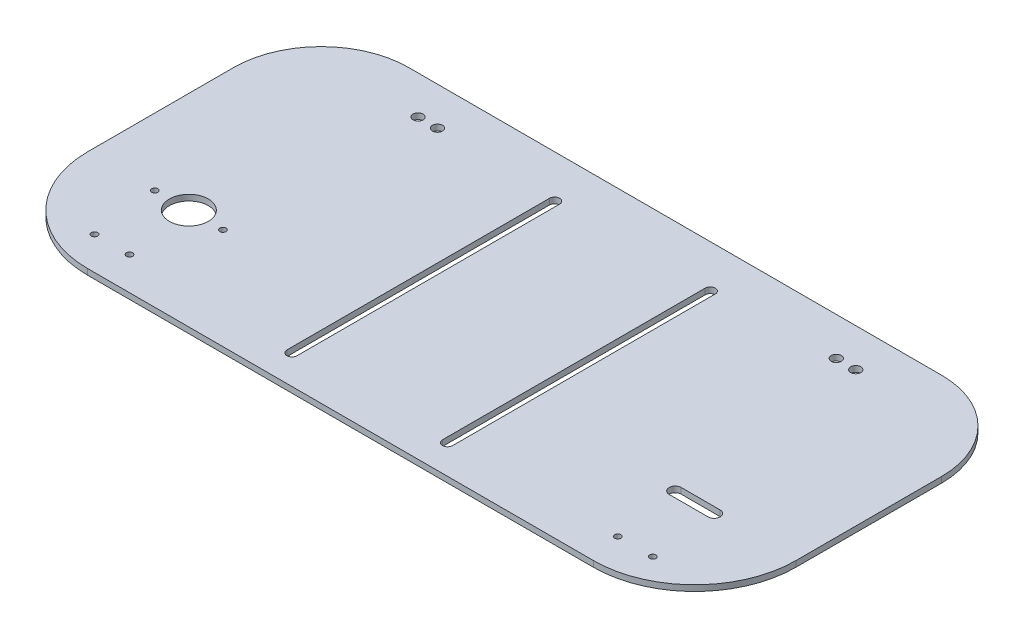
SolidWorks part; units mm, degrees
ref_plane "Front Plane" through (0, 0, 0) normal (0, 0, 1) x (1, 0, 0)
ref_plane "Top Plane" through (0, 0, 0) normal (0, 1, 0) x (1, 0, 0)
ref_plane "Right Plane" through (0, 0, 0) normal (1, 0, 0) x (0, 0, -1)
sketch "Sketch1" plane through (0, 0, 0) normal (0, 1, 0) x (1, 0, 0)
  line L0 (0, 0) -> (260, 0) construction
  line L5 (0, 52) -> (260, 52)
  line L6 (0, -52) -> (260, -52)
  line L7 (270, 0) -> (250, 0) construction
  line L8 (270, -3.1) -> (250, -3.1)
  line L9 (270, 3.1) -> (250, 3.1)
  line L11 (-52, 0) -> (312, 0) construction
  line L12 (-52, 0) -> (-52, 120)
  line L13 (-52, 120) -> (312, 120)
  line L14 (312, 0) -> (312, 120)
  arc A0 (0, 52) -> (0, -52) centre (0, 0) ccw
  arc A1 (260, -52) -> (260, 52) centre (260, 0) ccw
  circle A2 centre (0, 0) radius 3.1
  arc A4 (270, -3.1) -> (270, 3.1) centre (270, 0) ccw
  arc A5 (250, 3.1) -> (250, -3.1) centre (250, 0) ccw
  point P2 (130, 0)
  point P12 (260, 0)
  dimension "D2" = 52
  dimension "D3" = 6.2
  dimension "D1" = 260
  dimension "D4" = 20
  dimension "D5" = 120
  dimension "D6" = 270
extrude "Boss-Extrude1" add sketch "Sketch1" along normal blind 3 contours L6 A1 L5 A0 A5 L9 A4 L8 A2 | A1 L14 L13 L12 A0 L5
sketch "Sketch2" plane through (0, 3, 0) normal (0, 1, 0) x (1, 0, 0)
  line L0 (-52, 105) -> (312, 105) construction
  line L1 (-52, 0) -> (-52, 120) construction
  line L2 (312, 0) -> (312, 120) construction
  line L3 (-52, 120) -> (312, 120) construction
  line L4 (130, 120) -> (130, -52) construction
  line L5 (0, -52) -> (260, -52) construction
  line L6 (90, 120) -> (90, -52) construction
  line L7 (170, 120) -> (170, -52) construction
  line L11 (-36.5377, -37) -> (296.5377, -37) construction
  line L12 (90, -37) -> (90, 98) construction
  line L13 (87.4, -37) -> (87.4, 98)
  line L14 (92.6, -37) -> (92.6, 98)
  line L15 (170, -37) -> (170, 98) construction
  line L16 (172.6, -37) -> (172.6, 98)
  line L17 (167.4, -37) -> (167.4, 98)
  arc A2 (-52, 0) -> (0, -52) centre (0, 0) ccw construction
  arc A3 (260, -52) -> (312, 0) centre (260, 0) ccw construction
  arc A4 (87.4, -37) -> (92.6, -37) centre (90, -37) ccw
  arc A5 (92.6, 98) -> (87.4, 98) centre (90, 98) ccw
  arc A6 (172.6, -37) -> (167.4, -37) centre (170, -37) cw
  arc A7 (167.4, 98) -> (172.6, 98) centre (170, 98) cw
  point P33 (90, 30.5)
  point P40 (170, 30.5)
  dimension "D4" = 2.6
  dimension "D1" = 15
  dimension "D2" = 40
  dimension "D3" = 40
  dimension "D6" = 15
  dimension "D7" = 135
extrude "Cut-Extrude1" cut sketch "Sketch2" against normal through all
fillet "Fillet1" radius 45 2 edges at (312, 1.5, -120) (-52, 1.5, -120)
sketch "Sketch3" plane through (0, 3, 0) normal (0, 1, 0) x (1, 0, 0)
  circle A0 centre (0, 0) radius 10
  dimension "D1" = 20
extrude "Cut-Extrude2" cut sketch "Sketch3" against normal through all
sketch "Sketch4" plane through (0, 0, 0) normal (0, -1, 0) x (1, 0, 0)
  circle A0 centre (17.4, -100.4) radius 2.6
  circle A1 centre (27.4, -100.4) radius 2.6
  circle A2 centre (232.4, -100.4) radius 2.6
  circle A3 centre (242.4, -100.4) radius 2.6
  circle A4 centre (242.4, -100.4) radius 2.6 construction
  circle A5 centre (232.4, -100.4) radius 2.6 construction
  circle A6 centre (17.4, -100.4) radius 2.6 construction
  circle A7 centre (27.4, -100.4) radius 2.6 construction
extrude "Cut-Extrude3" cut sketch "Sketch4" against normal through all
sketch "Sketch5" plane through (0, 3, 0) normal (0, 1, 0) x (1, 0, 0)
  line L0 (-17.5, 0) -> (0, 0) construction
  line L1 (0, 0) -> (17.5, 0) construction
  circle A0 centre (-17.5, 0) radius 1.6
  circle A1 centre (17.5, 0) radius 1.6
  point P4 (0, 0)
  point P6 (0, 0)
  dimension "D1" = 17.5
  dimension "D2" = 3.2
extrude "Cut-Extrude4" cut sketch "Sketch5" against normal through all
sketch "Sketch6" plane through (0, 3, 0) normal (0, 1, 0) x (1, 0, 0)
  circle A0 centre (-13.5, -35) radius 1.6
  circle A1 centre (4.5, -35) radius 1.6
  circle A2 centre (255.5, -35) radius 1.6
  circle A3 centre (273.5, -35) radius 1.6
  point P11 (-14.4234, -34.9356)
  point P12 (-14.0384, -35)
  point P13 (-13.3937, -35)
  point P14 (-13.5, -35.1971)
  point P15 (-13.5, -35)
  dimension "D1" = 3.2
extrude "Cut-Extrude5" cut sketch "Sketch6" against normal through all
